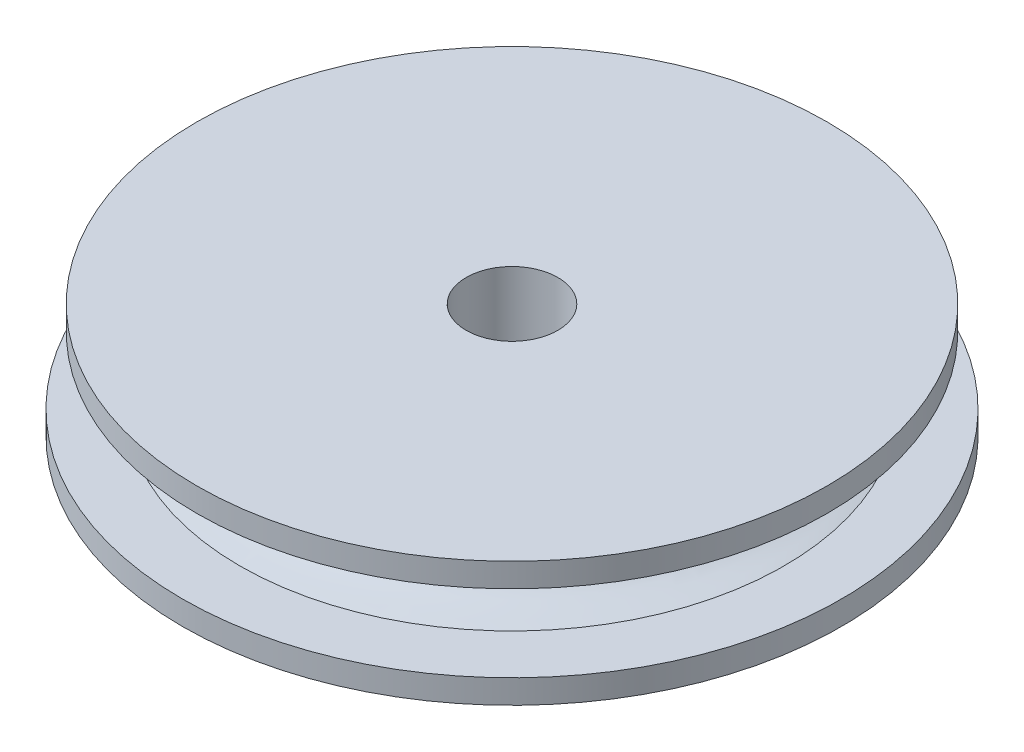
SolidWorks part; units mm, degrees
ref_plane "Front Plane" through (0, 0, 0) normal (0, 0, 1) x (1, 0, 0)
ref_plane "Top Plane" through (0, 0, 0) normal (0, 1, 0) x (1, 0, 0)
ref_plane "Right Plane" through (0, 0, 0) normal (1, 0, 0) x (0, 0, -1)
sketch "Sketch1" plane through (0, 0, 0) normal (0, 1, 0) x (1, 0, 0)
  circle A0 centre (0, 0) radius 9.5
extrude "Boss-Extrude1" add sketch "Sketch1" along normal blind 4
sketch "Sketch2" plane through (0, 0, 0) normal (0, 0, 1) x (1, 0, 0)
  line L0 (-9.5, 0) -> (9.5, 0) construction
  line L1 (9.5, 4) -> (-9.5, 4) construction
  line L2 (-9.5, 0) -> (9.5, 0) construction
  line L3 (9.5, 4) -> (-9.5, 4) construction
  line L4 (-9.5, 4) -> (-9.5, 0) construction
  line L5 (9.5, 0) -> (9.5, 4) construction
  line L6 (-9.5, 4) -> (-9.5, 0) construction
  line L7 (9.5, 0) -> (9.5, 4) construction
  line L8 (-9.5, 2) -> (9.5, 2) construction
  line L9 (-9.5, 4) -> (-9.5, 3.1672)
  line L10 (-9.5, 0) -> (-9.5, 0.8328)
  line L11 (-9.5, 3.1672) -> (-9.5, 0.8328)
  spline S0 degree 3 poles (-9.5, 3.1672) (-8.911, 2.9848) (-7.9402, 2.8431) (-8, 2) knots 0 0 0 0 1 1 1 1
  spline S1 degree 3 poles (-9.5, 0.8328) (-8.911, 1.0152) (-7.9402, 1.1569) (-8, 2) knots 0 0 0 0 1 1 1 1
  point P6 (-8, 2)
  point P10 (-10.6735, 2.075)
  point P12 (-8, 2)
  point P16 (0, 0)
  dimension "D1" = 1.5
ref_axis "Revolving cut axis" through (0, 4.2, 0) along (0, -1, 0)
revolve "Cut-Revolve3" cut sketch "Sketch2" angle 360 about axis through (0, 4.2, 0) along (0, -1, 0)
sketch "Sketch3" plane through (0, 4, 0) normal (0, 1, 0) x (1, 0, 0)
  circle A0 centre (0, 0) radius 1.6
extrude "Cut-Extrude1" cut sketch "Sketch3" against normal through all
sketch "Sketch4" plane through (0, 4, 0) normal (0, 1, 0) x (1, 0, 0)
  circle A2 centre (0, 0) radius 11
  circle A3 centre (0, 0) radius 11
  circle A4 centre (0, 0) radius 1.6
  circle A5 centre (0, 0) radius 1.6
  dimension "D1" = 1.5
  dimension "D2" = 0
ref_point "Extension top point"
extrude "Extension top" add sketch "Sketch4" against normal up to vertex (0.8328 mm away)
sketch "Sketch5" plane through (0, 0, 0) normal (0, -1, 0) x (1, 0, 0)
  circle A2 centre (0, 0) radius 1.6
  circle A3 centre (0, 0) radius 1.6
  circle A5 centre (0, 0) radius 11.5
  circle A6 centre (0, 0) radius 11.5
  dimension "D1" = 0
  dimension "D2" = 2
ref_point "Extension bottom point"
extrude "Boss-Extrude4" add sketch "Sketch5" against normal up to vertex (0.8328 mm away)
